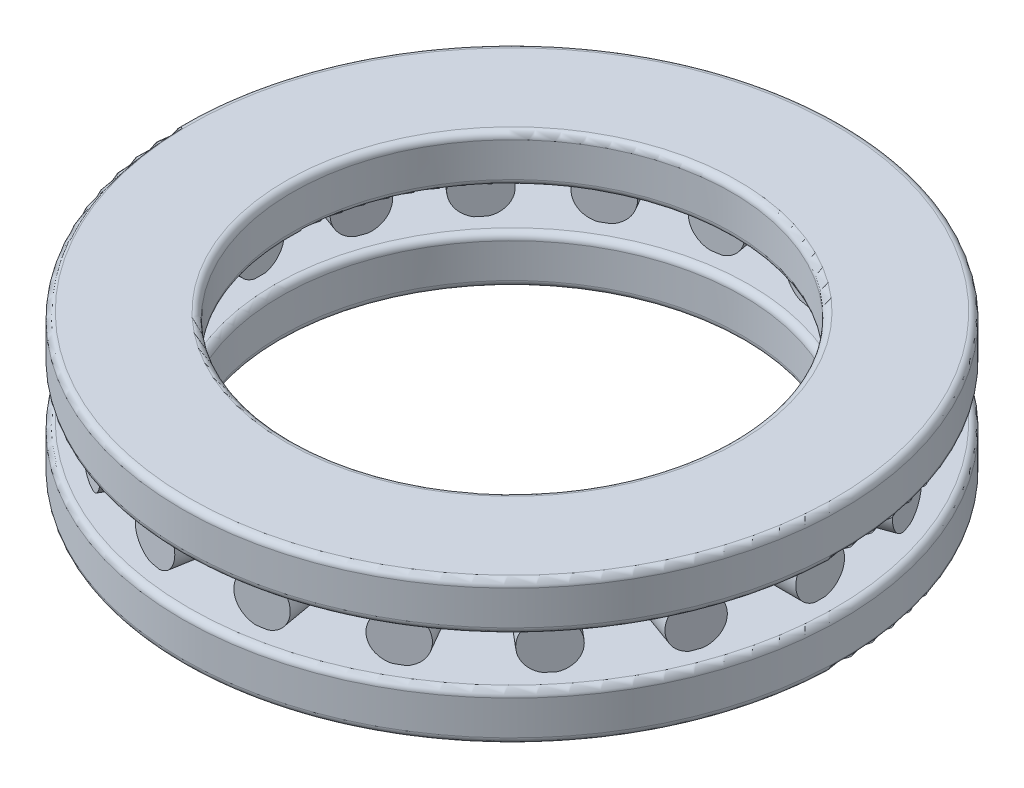
SolidWorks part; units mm, degrees
material "AISI 304"
ref_plane "基准面1" through (0, 0, 0) normal (0, 0, 1) x (1, 0, 0)
ref_plane "基准面2" through (0, 0, 0) normal (0, 1, 0) x (1, 0, 0)
ref_plane "基准面3" through (0, 0, 0) normal (1, 0, 0) x (0, 0, -1)
sketch "尺寸草图" plane through (0, 0, 0) normal (0, 0, 1) x (1, 0, 0)
  line L0 (0, 0) -> (60, 0)
  point P3 (42, 0)
  point P4 (13, 0)
  point P5 (60, 0)
  point P6 (40, 0)
  point P7 (0.6, 0)
  dimension "DD" = 60
  dimension "d1" = 42
  dimension "d" = 40
  dimension "T" = 13
  dimension "r" = 0.6
  dimension "DD1" = 60
sketch "草图1" plane through (0, 0, 0) normal (0, 0, 1) x (1, 0, 0)
  line L0 (30, 13) -> (30, 0) construction
  line L1 (0, 0) -> (60, 0)
  line L2 (0, 0) -> (0, 13)
  line L3 (0, 13) -> (60, 13)
  line L4 (60, 0) -> (60, 13)
  line L5 (0, 6.5) -> (60, 6.5) construction
  line L6 (9, 13) -> (9, 0)
  line L7 (51, 8.6667) -> (51, 0)
  line L8 (0, 4.3333) -> (60, 4.3333)
  line L9 (0, 8.6667) -> (60, 8.6667)
  line L10 (10, 13) -> (10, 0)
  line L11 (50, 9) -> (50, 0)
  line L12 (4.5, 13) -> (4.5, 0) construction
  line L13 (55.5, 8.6667) -> (55.5, 0)
  line L14 (2, 13) -> (2, 0)
  line L15 (7, 13) -> (7, 0)
  line L16 (0, 9) -> (0, 0)
  line L17 (60, 8.6667) -> (60, 0)
  dimension "D1" = 60
  dimension "D2" = 13
  dimension "D3" = 40
  dimension "D4" = 42
  dimension "D5" = 4.3333
  dimension "D6" = 51
  dimension "D7" = 5
  dimension "D8" = 60
sketch "草图2" plane through (0, 0, 0) normal (0, 0, 1) x (1, 0, 0)
  line L0 (30, 13) -> (30, 0) construction
  line L1 (10, 13) -> (10, 0) construction
  line L2 (0, 8.6667) -> (60, 8.6667) construction
  line L5 (30, 13) -> (30, 0) construction
  line L6 (10, 13) -> (10, 8.6667)
  line L7 (0, 8.6667) -> (10, 8.6667)
  line L8 (0, 13) -> (60, 13) construction
  line L9 (0, 13) -> (10, 13)
  line L10 (0, 9) -> (0, 0) construction
  line L11 (0, 13) -> (0, 8.6667)
revolve "基体-旋转" add sketch "草图2" angle 360 about L5
sketch "草图3" plane through (0, 0, 0) normal (0, 0, 1) x (1, 0, 0)
  line L0 (0, 6.5) -> (60, 6.5) construction
  line L1 (2, 13) -> (2, 0) construction
  line L2 (7, 13) -> (7, 0) construction
  line L4 (0, 8.6667) -> (60, 8.6667) construction
  line L5 (0, 6.5) -> (60, 6.5) construction
  line L6 (2, 8.6667) -> (2, 6.5) construction
  line L7 (7, 8.6667) -> (7, 6.5) construction
  line L8 (7.05, 8.7167) -> (7.05, 6.5)
  line L9 (2, 8.6667) -> (7, 8.6667) construction
  line L10 (1.95, 8.7167) -> (7.05, 8.7167)
  line L11 (1.95, 8.7167) -> (1.95, 6.5)
  line L12 (7.05, 6.5) -> (1.95, 6.5)
  dimension "D1" = 0.05
revolve "凸台-旋转1" add sketch "草图3" angle 360 about L5
sketch "草图4" plane through (0, 0, 0) normal (0, 0, 1) x (1, 0, 0)
  line L0 (30, 13) -> (30, 0) construction
  line L1 (9, 13) -> (9, 0) construction
  line L2 (0, 4.3333) -> (60, 4.3333) construction
  line L3 (0, 0) -> (60, 0) construction
  line L4 (0, 0) -> (0, 13) construction
  line L5 (30, 13) -> (30, 0) construction
  line L6 (9, 4.3333) -> (9, 0)
  line L7 (0, 4.3333) -> (9, 4.3333)
  line L8 (0, 0) -> (9, 0)
  line L9 (0, 0) -> (0, 4.3333)
revolve "凸台-旋转2" add sketch "草图4" angle 360 about L5
pattern_circular "阵列(圆周)1" count 18 over 360 about axis through (30, 0, 0) along (0, 1, 0) of "凸台-旋转1"
fillet "圆角1" radius 0.6 8 edges at (30, 4.3333, 30) (30, 0, 21) (30, 4.3333, 21) (30, 0, 30) (30, 13, 30) (30, 8.6667, 30) (30, 8.6667, 20) (30, 13, 20)
